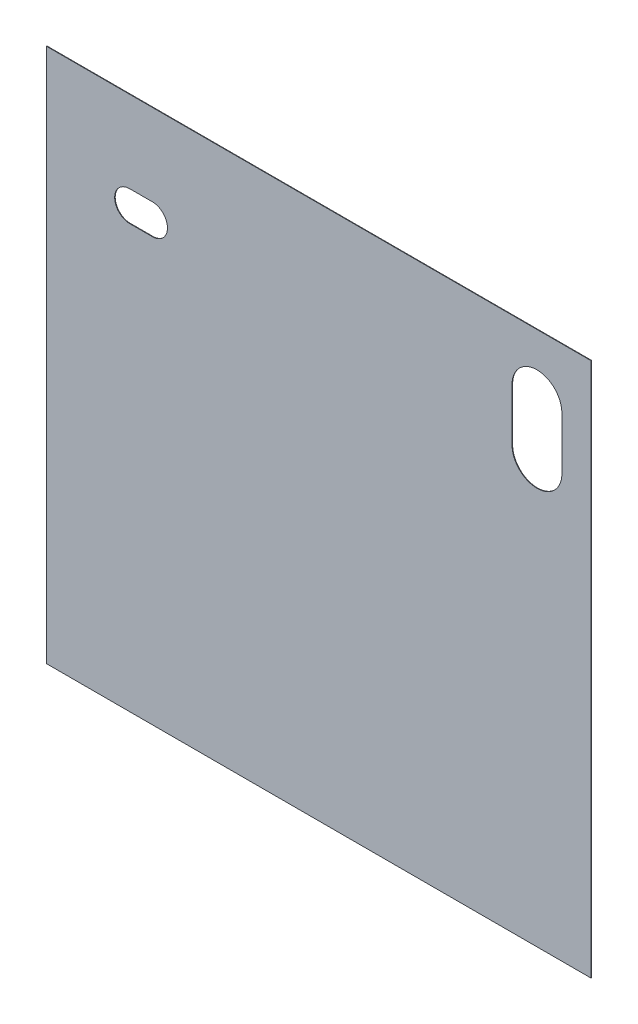
SolidWorks part; units mm, degrees
ref_plane "Front Plane" through (0, 0, 0) normal (0, 0, 1) x (1, 0, 0)
ref_plane "Top Plane" through (0, 0, 0) normal (0, 1, 0) x (1, 0, 0)
ref_plane "Right Plane" through (0, 0, 0) normal (1, 0, 0) x (0, 0, -1)
sketch "Sketch1" plane through (0, 0, 0) normal (0, 0, 1) x (1, 0, 0)
  line L1 (0, 0) -> (509, 0)
  line L2 (0, 0) -> (0, 500)
  line L3 (0, 500) -> (509, 500)
  line L4 (509, 0) -> (509, 500)
  line L6 (458.585, 444.0069) -> (458.585, 394.6755) construction
  line L7 (481.865, 444.0069) -> (481.865, 394.6755)
  line L8 (435.305, 444.0069) -> (435.305, 394.6755)
  arc A0 (481.865, 444.0069) -> (435.305, 444.0069) centre (458.585, 444.0069) ccw
  arc A1 (435.305, 394.6755) -> (481.865, 394.6755) centre (458.585, 394.6755) ccw
  point P9 (458.585, 419.3412)
extrude "Boss-Extrude1" add sketch "Sketch1" along normal blind 0.5
ref_plane "Plane1" through (509, 0, 0) normal (-1, 0, 0) x (0, 1, 0)
ref_plane "Plane2" through (0, 0, 0) normal (1, 0, 0) x (0, -1, 0)
sketch "Sketch8" plane through (0, 0, 0.5) normal (0, 0, 1) x (1, 0, 0)
  line L0 (77.7857, 409.4252) -> (98.9589, 409.4252) construction
  line L1 (77.7857, 423.5325) -> (98.9589, 423.5325)
  line L2 (77.7857, 395.3178) -> (98.9589, 395.3178)
  arc A0 (77.7857, 423.5325) -> (77.7857, 395.3178) centre (77.7857, 409.4252) ccw
  arc A1 (98.9589, 395.3178) -> (98.9589, 423.5325) centre (98.9589, 409.4252) ccw
  point P2 (88.3723, 409.4252)
extrude "Cut-Extrude4" cut sketch "Sketch8" against normal blind 10
